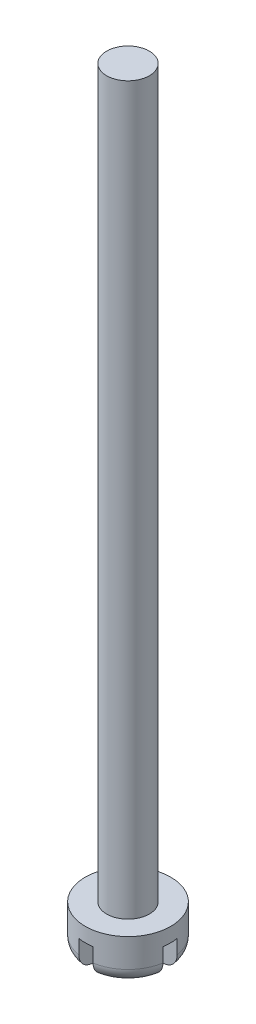
SolidWorks part; units mm, degrees
ref_plane "Plan de face" through (0, 0, 0) normal (0, 0, 1) x (1, 0, 0)
ref_plane "Plan de dessus" through (0, 0, 0) normal (0, 1, 0) x (1, 0, 0)
ref_plane "Plan de droite" through (0, 0, 0) normal (1, 0, 0) x (0, 0, -1)
ref_plane "Plan1" through (0, -1.5, 0) normal (0, -1, 0) x (1, 0, 0)
sketch "Esquisse1" plane through (0, -1.5, 0) normal (0, -1, 0) x (1, 0, 0)
  circle A0 centre (-17.0693, 10.6565) radius 1.5
  dimension "D1" = 3
extrude "Boss.-Extru.1" add sketch "Esquisse1" against normal blind 1.5
sketch "Esquisse2" plane through (0, 0, 0) normal (0, 1, 0) x (1, 0, 0)
  circle A0 centre (-17.0693, -10.6565) radius 0.75
  dimension "D1" = 1.5
extrude "Boss.-Extru.2" add sketch "Esquisse2" along normal blind 25.5
sketch "Esquisse3" plane through (0, -1.5, 0) normal (0, -1, 0) x (1, 0, 0)
  line L1 (-16.8193, 12.4652) -> (-17.3193, 12.4652)
  line L2 (-16.8193, 12.4652) -> (-16.8193, 8.8478)
  line L3 (-16.8193, 8.8478) -> (-17.3193, 8.8478)
  line L4 (-17.3193, 12.4652) -> (-17.3193, 8.8478)
  line L5 (-16.8193, 12.4652) -> (-17.3193, 8.8478) construction
  line L6 (-16.8193, 8.8478) -> (-17.3193, 12.4652) construction
  line L7 (-18.9931, 10.4065) -> (-15.1454, 10.4065)
  line L8 (-18.9931, 10.4065) -> (-18.9931, 10.9065)
  line L9 (-18.9931, 10.9065) -> (-15.1454, 10.9065)
  line L10 (-15.1454, 10.4065) -> (-15.1454, 10.9065)
  line L11 (-18.9931, 10.4065) -> (-15.1454, 10.9065) construction
  line L12 (-18.9931, 10.9065) -> (-15.1454, 10.4065) construction
  point P0 (-17.0693, 10.6565)
  point P6 (-17.0693, 10.6565)
  circle M3 centre (-17.0693, 10.6565) radius 1.5
  dimension "D1" = 0.5
  dimension "D2" = 0.5
extrude "Enlèv. mat.-Extru.1" cut sketch "Esquisse3" against normal blind 1 contours L7 L4 L2 M3 | L4 L9 L2 M3 | L9 L2 L7 M3 | L9 L7 L4 M3 | L9 L4 L7 L2
fillet "Congé1" radius 0.5 4 edges at (-16.0086, -1.5, 11.7172) (-18.1299, -1.5, 11.7172) (-18.1299, -1.5, 9.5958) (-16.0086, -1.5, 9.5958)
